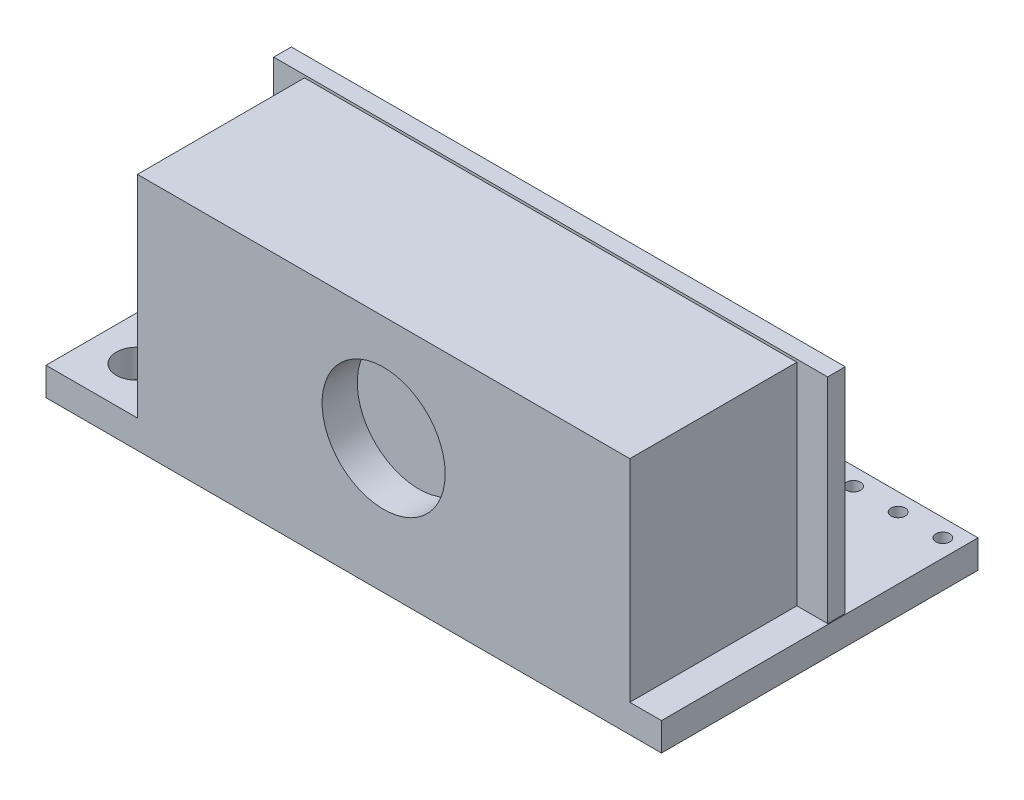
SolidWorks part; units mm, degrees
ref_plane "前视基准面" through (0, 0, 0) normal (0, 0, 1) x (1, 0, 0)
ref_plane "上视基准面" through (0, 0, 0) normal (0, 1, 0) x (1, 0, 0)
ref_plane "右视基准面" through (0, 0, 0) normal (1, 0, 0) x (0, 0, -1)
other "Configuration Table"
sketch "草图2" plane through (0, 0, 0) normal (0, 0, 1) x (1, 0, 0)
  line L1 (-14, 6) -> (14, 6)
  line L2 (-14, 6) -> (-14, -6)
  line L3 (-14, -6) -> (14, -6)
  line L4 (14, 6) -> (14, -6)
  line L5 (-14, 6) -> (14, -6) construction
  line L6 (-14, -6) -> (14, 6) construction
  point P0 (0, 0)
  dimension "D1" = 28
  dimension "D2" = 12
extrude "凸台-拉伸1" add sketch "草图2" along normal blind 9.5
sketch "草图3" plane through (0, 0, 0) normal (0, 0, -1) x (-1, 0, 0)
  line L1 (-15.75, 6.15) -> (15.75, 6.15)
  line L2 (-15.75, 6.15) -> (-15.75, -6.15)
  line L3 (-15.75, -6.15) -> (15.75, -6.15)
  line L4 (15.75, 6.15) -> (15.75, -6.15)
  line L5 (-15.75, 6.15) -> (15.75, -6.15) construction
  line L6 (-15.75, -6.15) -> (15.75, 6.15) construction
  point P0 (0, 0)
  dimension "D1" = 31.5
  dimension "D2" = 12.3
extrude "凸台-拉伸2" add sketch "草图3" along normal blind 1
sketch "草图4" plane through (0, -6, 0) normal (0, -1, 0) x (1, 0, 0)
  line L0 (-1.7, 0.2708) -> (-1.7, -49999.7292) construction
  line L2 (-19.2, -8.5) -> (15.8, -8.5)
  line L3 (-19.2, -8.5) -> (-19.2, 9.5)
  line L4 (-19.2, 9.5) -> (15.8, 9.5)
  line L5 (15.8, -8.5) -> (15.8, 9.5)
  line L6 (-19.2, -8.5) -> (15.8, 9.5) construction
  line L7 (-19.2, 9.5) -> (15.8, -8.5) construction
  line L8 (-14, 9.5) -> (-14, 0) construction
  line L10 (-14, 9.5) -> (14, 9.5) construction
  circle A0 centre (-16.7, 6.85) radius 1.15
  circle A1 centre (14.8, -7.5) radius 0.4
  circle A2 centre (12.26, -7.5) radius 0.4
  circle A3 centre (9.72, -7.5) radius 0.4
  circle A4 centre (7.18, -7.5) radius 0.4
  circle A5 centre (4.64, -7.5) radius 0.4
  point P3 (-1.7, 0.5)
  dimension "D4" = 2.3
  dimension "D9" = 1
  dimension "D7" = 0.8
  dimension "D1" = 35
  dimension "D2" = 18
  dimension "D3" = 5.2
  dimension "D5" = 2.5
  dimension "D6" = 2.65
  dimension "D8" = 1
  dimension "D10" = 5
extrude "凸台-拉伸3" add sketch "草图4" along normal blind 1.6
sketch "草图6" plane through (0, 0, 9.5) normal (0, 0, 1) x (1, 0, 0)
  line L0 (0, 0) -> (50000, 0) construction
  line L1 (0, 0) -> (0, -50000) construction
  circle A0 centre (0, 0) radius 3.5
  dimension "D1" = 7
extrude "切除-拉伸1" cut sketch "草图6" against normal blind 2
